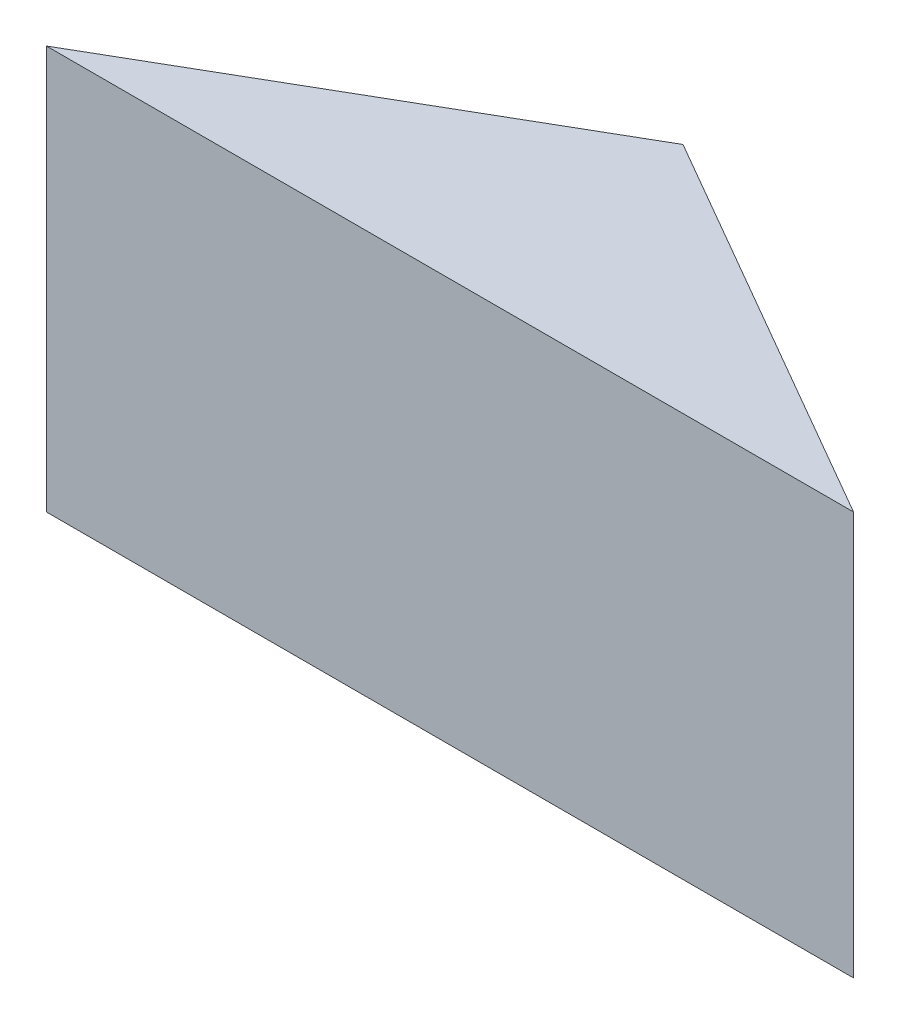
SolidWorks part; units mm, degrees
ref_plane "Přední rovina" through (0, 0, 0) normal (0, 0, 1) x (1, 0, 0)
ref_plane "Horní rovina" through (0, 0, 0) normal (0, 1, 0) x (1, 0, 0)
ref_plane "Pravá rovina" through (0, 0, 0) normal (1, 0, 0) x (0, 0, -1)
sketch "Sketch1" plane through (0, 0, 0) normal (0, 1, 0) x (1, 0, 0)
  line L0 (-20, 0) -> (20, 0)
  line L1 (20, 0) -> (0, 11.547)
  line L2 (0, 11.547) -> (0, 0) construction
  line L3 (-20, 0) -> (0, 11.547)
  point P4 (0, 0)
  point P5 (0, 0)
  point P6 (0, 16.8591)
  dimension "D1" = 30
  dimension "D2" = 20
extrude "Boss-Extrude1" add sketch "Sketch1" along normal blind 20 contours L2 L3 L0 | L1 L2 L0
equation "\"ěé\"=30"
